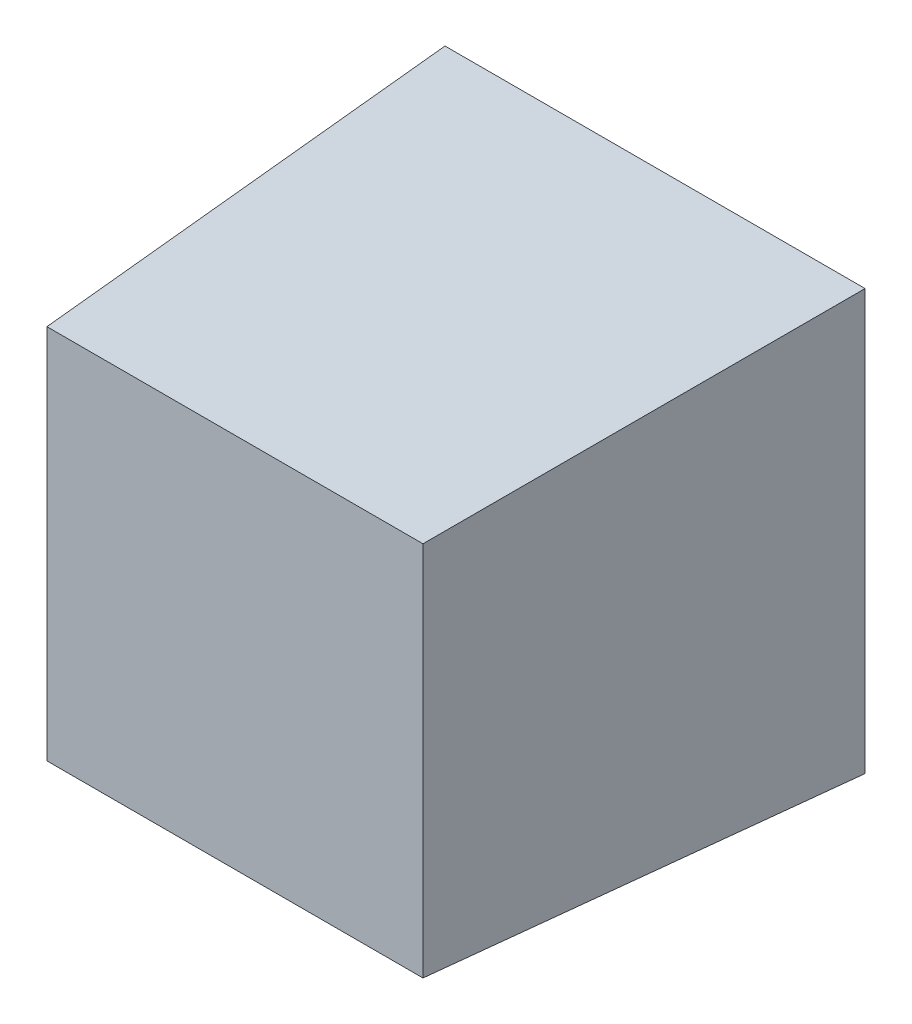
SolidWorks part; units mm, degrees
ref_plane "前视基准面" through (0, 0, 0) normal (0, 0, 1) x (1, 0, 0)
ref_plane "上视基准面" through (0, 0, 0) normal (0, 1, 0) x (1, 0, 0)
ref_plane "右视基准面" through (0, 0, 0) normal (1, 0, 0) x (0, 0, -1)
other "Configuration Table"
sketch "草图1" plane through (0, 0, 0) normal (0, 0, 1) x (1, 0, 0)
  line L1 (0, 0) -> (10, 0)
  line L2 (0, 0) -> (0, 10)
  line L3 (0, 10) -> (10, 10)
  line L4 (10, 0) -> (10, 10)
extrude "凸台-拉伸1" add sketch "草图1" along normal blind 10 draft 3
